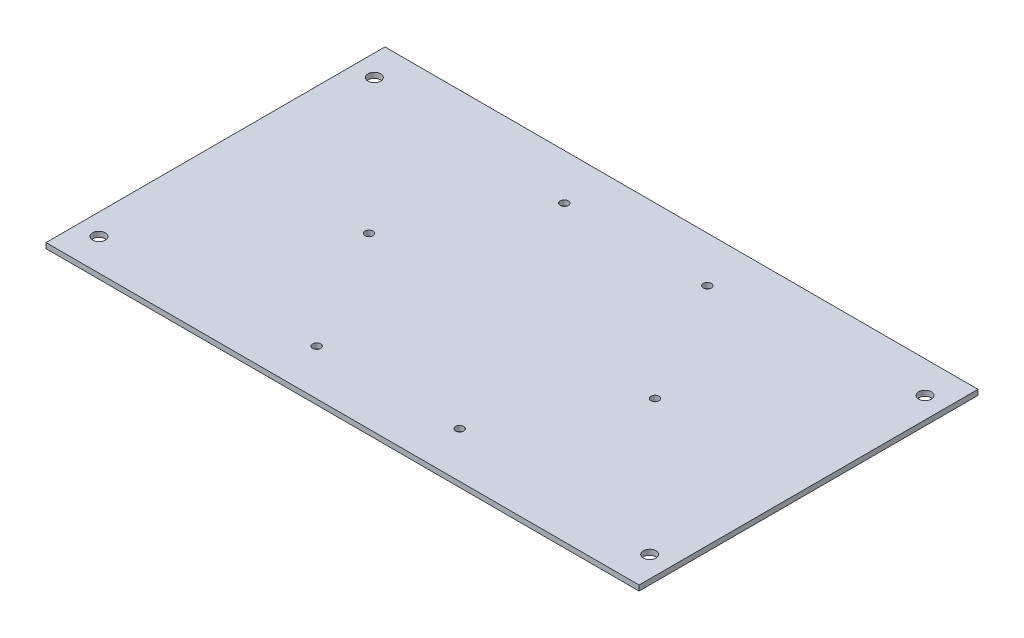
SolidWorks part; units mm, degrees
ref_plane "Front Plane" through (0, 0, 0) normal (0, 0, 1) x (1, 0, 0)
ref_plane "Top Plane" through (0, 0, 0) normal (0, 1, 0) x (1, 0, 0)
ref_plane "Right Plane" through (0, 0, 0) normal (1, 0, 0) x (0, 0, -1)
sketch "Sketch1" plane through (0, 0, 0) normal (0, 1, 0) x (1, 0, 0)
  line L0 (0, 0) -> (42.8625, 74.24) construction
  line L1 (-177.8, 101.6) -> (177.8, 101.6)
  line L2 (-177.8, 101.6) -> (-177.8, -101.6)
  line L3 (-177.8, -101.6) -> (177.8, -101.6)
  line L4 (177.8, 101.6) -> (177.8, -101.6)
  line L5 (-177.8, 101.6) -> (177.8, -101.6) construction
  line L6 (-177.8, -101.6) -> (177.8, 101.6) construction
  line L7 (0, 0) -> (85.725, 0) construction
  line L8 (0, 0) -> (74.24, 42.8625) construction
  line L9 (0, 0) -> (85.725, 0) construction
  line L10 (0, 0) -> (74.24, -42.8625) construction
  line L11 (0, 0) -> (42.8625, -74.24) construction
  line L12 (0, 0) -> (0, -85.725) construction
  line L13 (0, 0) -> (-42.8625, -74.24) construction
  line L14 (0, 0) -> (-74.24, -42.8625) construction
  line L15 (0, 0) -> (-85.725, 0) construction
  line L16 (0, 0) -> (-74.24, 42.8625) construction
  line L17 (0, 0) -> (-42.8625, 74.24) construction
  line L18 (0, 0) -> (0, 85.725) construction
  circle A1 centre (42.8625, 74.24) radius 2.413
  circle A2 centre (74.24, 42.8625) radius 2.413 [skipped]
  circle A3 centre (85.725, 0) radius 2.413
  circle A4 centre (74.24, -42.8625) radius 2.413 [skipped]
  circle A5 centre (42.8625, -74.24) radius 2.413
  circle A6 centre (0, -85.725) radius 2.413 [skipped]
  circle A7 centre (-42.8625, -74.24) radius 2.413
  circle A8 centre (-74.24, -42.8625) radius 2.413 [skipped]
  circle A9 centre (-85.725, 0) radius 2.413
  circle A10 centre (-74.24, 42.8625) radius 2.413 [skipped]
  circle A11 centre (-42.8625, 74.24) radius 2.413
  circle A12 centre (0, 85.725) radius 2.413 [skipped]
  point P0 (0, 0)
  point P36 (0, 0)
  dimension "D6" = 4.826
  dimension "D1" = 203.2
  dimension "D2" = 355.6
  dimension "D4" = 60
  dimension "D5" = 85.725
  dimension "D7" = 12
extrude "Boss-Extrude1" add sketch "Sketch1" along normal blind 3.175
sketch "Sketch2" plane through (0, 3.175, 0) normal (0, 1, 0) x (1, 0, 0)
  line L0 (165.1, 0) -> (-165.1, 0) construction
  line L1 (165.1, 82.55) -> (-165.1, 82.55)
  line L2 (165.1, 82.55) -> (165.1, -82.55)
  line L3 (165.1, -82.55) -> (-165.1, -82.55)
  line L4 (-165.1, 82.55) -> (-165.1, -82.55)
  line L5 (165.1, 82.55) -> (-165.1, -82.55) construction
  line L6 (165.1, -82.55) -> (-165.1, 82.55) construction
  line L7 (0, 82.55) -> (0, -82.55) construction
  circle A0 centre (165.1, 82.55) radius 3.81
  circle A1 centre (-165.1, 82.55) radius 3.81
  circle A2 centre (-165.1, -82.55) radius 3.81
  circle A3 centre (165.1, -82.55) radius 3.81
  point P0 (0, 0)
  dimension "D2" = 330.2
  dimension "D3" = 7.62
  dimension "D1" = 165.1
extrude "Cut-Extrude1" cut sketch "Sketch2" against normal through all contours A0 | A1 | A2 | A3
sketch "Sketch3" plane through (0, 3.175, 0) normal (0, 1, 0) x (1, 0, 0)
  line L0 (0, 0) -> (0, 101.6) construction
  line L1 (-167.3037, 33.655) -> (-99.9937, 33.655) construction
  line L2 (-167.3037, 33.655) -> (-167.3037, -33.655) construction
  line L3 (-167.3037, -33.655) -> (-99.9937, -33.655) construction
  line L4 (-99.9937, 33.655) -> (-99.9937, -33.655) construction
  line L5 (-167.3037, 33.655) -> (-99.9937, -33.655) construction
  line L6 (-167.3037, -33.655) -> (-99.9937, 33.655) construction
  line L7 (177.8, 101.6) -> (-177.8, 101.6) construction
  line L8 (167.3037, -33.655) -> (99.9937, 33.655) construction
  line L9 (167.3037, 33.655) -> (99.9937, -33.655) construction
  line L10 (99.9937, 33.655) -> (99.9937, -33.655) construction
  line L11 (167.3037, -33.655) -> (99.9937, -33.655) construction
  line L12 (167.3037, 33.655) -> (167.3037, -33.655) construction
  line L13 (167.3037, 33.655) -> (99.9937, 33.655) construction
  circle A0 centre (-167.3037, 33.655) radius 3.175
  circle A1 centre (-167.3037, -33.655) radius 3.175
  circle A2 centre (-99.9937, -33.655) radius 3.175
  circle A3 centre (-99.9937, 33.655) radius 3.175
  circle A4 centre (99.9937, 33.655) radius 3.175
  circle A5 centre (99.9937, -33.655) radius 3.175
  circle A6 centre (167.3037, -33.655) radius 3.175
  circle A7 centre (167.3037, 33.655) radius 3.175
  point P0 (-133.6487, 0)
  point P22 (133.6487, 0)
  dimension "D2" = 6.35
  dimension "D1" = 67.31
